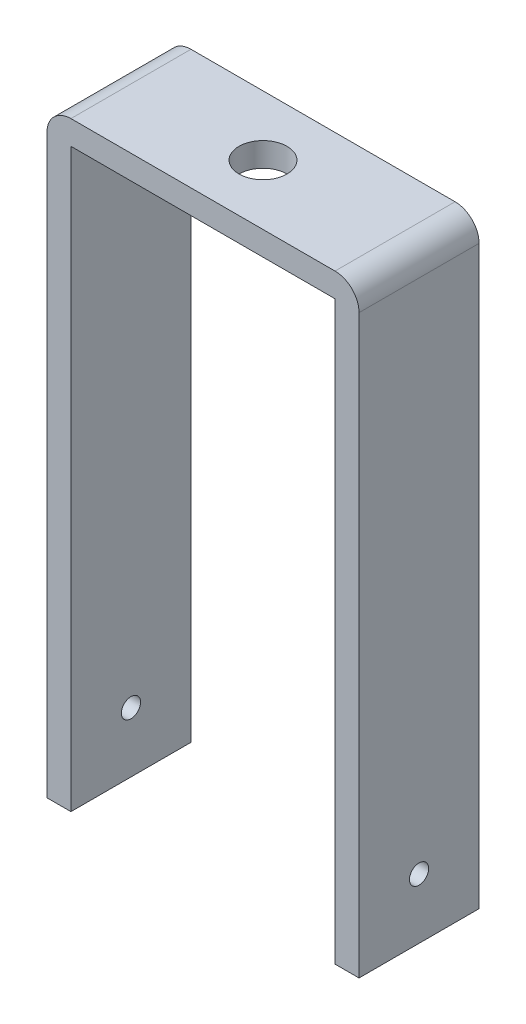
SolidWorks part; units mm, degrees
ref_plane "Front Plane" through (0, 0, 0) normal (0, 0, 1) x (1, 0, 0)
ref_plane "Top Plane" through (0, 0, 0) normal (0, 1, 0) x (1, 0, 0)
ref_plane "Right Plane" through (0, 0, 0) normal (1, 0, 0) x (0, 0, -1)
sketch "Sketch1" plane through (0, 0, 0) normal (0, 0, 1) x (1, 0, 0)
  line L1 (0, 0) -> (10, 0)
  line L2 (0, 0) -> (0, -250)
  line L3 (0, -250) -> (10, -250)
  line L4 (10, 0) -> (10, -250)
  line L5 (10, 0) -> (120, 0)
  line L6 (10, 0) -> (10, -10)
  line L7 (10, -10) -> (120, -10)
  line L8 (120, 0) -> (120, -10)
  line L9 (120, 0) -> (130, 0)
  line L10 (120, 0) -> (120, -250)
  line L11 (120, -250) -> (130, -250)
  line L12 (130, 0) -> (130, -250)
  dimension "D1" = 10
  dimension "D2" = 250
  dimension "D3" = 10
  dimension "D4" = 110
  dimension "D5" = 10
  dimension "D6" = 250
extrude "Boss-Extrude1" add sketch "Sketch1" along normal blind 50 contours L8 L5 L4 L7 | L4 L1 L2 L3 | L12 L9 L8 L10 L11
fillet "Fillet1" radius 10 2 edges at (0, 0, 25) (130, 0, 25)
sketch "Sketch2" plane through (130, 0, 0) normal (1, 0, 0) x (0, 0, -1)
  line L0 (-50, -250) -> (0, -250) construction
  line L2 (-50, -10) -> (-50, -250) construction
  circle A0 centre (-25, -225) radius 4
  dimension "D2" = 25
  dimension "D1" = 25
extrude "Cut-Extrude1" cut sketch "Sketch2" against normal blind 149
sketch "Sketch3" plane through (0, 0, 0) normal (0, 1, 0) x (1, 0, 0)
  line L0 (10, -50) -> (120, -50) construction
  line L1 (120, -50) -> (120, 0) construction
  circle A0 centre (65, -25) radius 10
  dimension "D1" = 25
  dimension "D2" = 55
extrude "Cut-Extrude2" cut sketch "Sketch3" against normal blind 10
